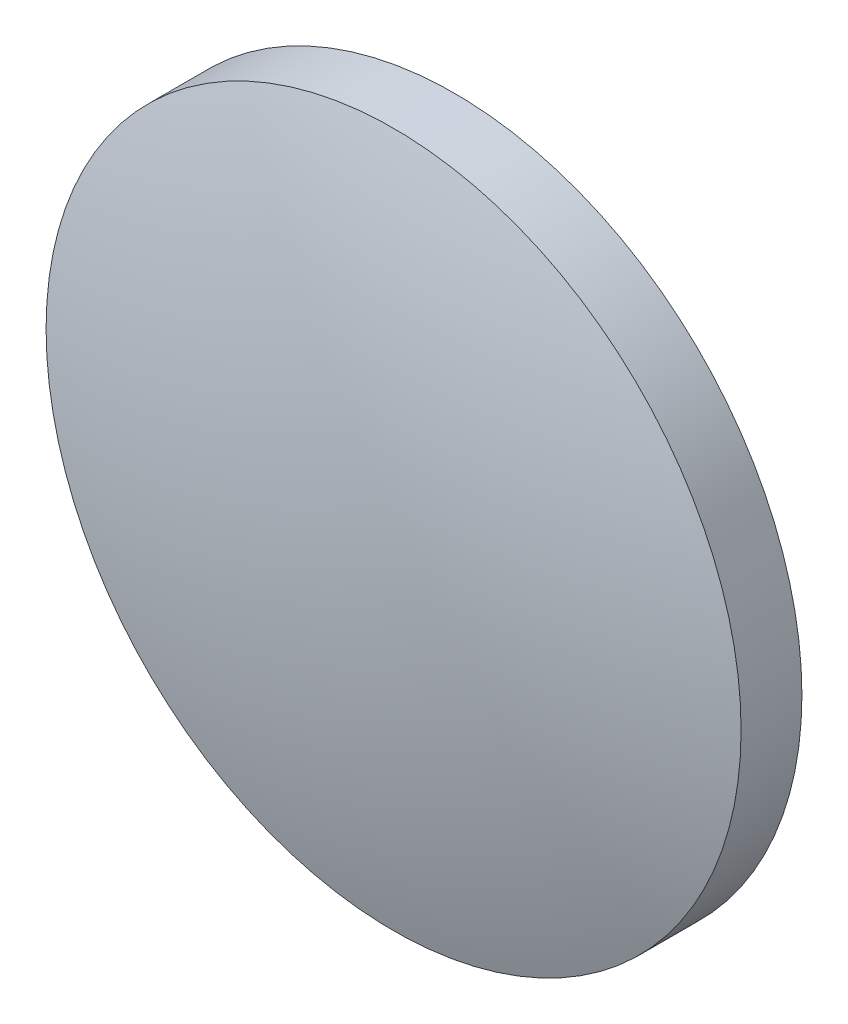
SolidWorks part; units mm, degrees
ref_plane "Front Plane" through (0, 0, 0) normal (0, 0, 1) x (1, 0, 0)
ref_plane "Top Plane" through (0, 0, 0) normal (0, 1, 0) x (1, 0, 0)
ref_plane "Right Plane" through (0, 0, 0) normal (1, 0, 0) x (0, 0, -1)
sketch "Sketch1" plane through (0, 0, 0) normal (0, 0, 1) x (1, 0, 0)
  circle A0 centre (0, 0) radius 20
  dimension "D1" = 40
extrude "Boss-Extrude1" add sketch "Sketch1" along normal blind 2
sketch "Sketch2" plane through (0, 0, 0) normal (1, 0, 0) x (0, 0, -1)
  line L0 (62.9923, 18.1472) -> (62.9923, -18.1472) construction
  line L1 (-2, 20) -> (-2, -20)
  arc A0 (-2, -20) -> (-2, 20) centre (62.9923, 0) cw
  point P3 (-5.0077, 0)
  point P8 (62.9923, 0)
  dimension "D1" = 68
  dimension "D2" = 68
revolve "Revolve1" add sketch "Sketch2" angle 360 about L0
sketch "Sketch3" plane through (0, 0, 0) normal (0, 1, 0) x (1, 0, 0)
  line L1 (76.406, 19.3589) -> (-76.406, 19.3589)
  line L2 (76.406, 19.3589) -> (76.406, 108.8795)
  line L4 (-76.406, 19.3589) -> (-76.406, 108.8795)
  line L5 (76.406, 19.3589) -> (-76.406, 108.8795) construction
  line L6 (76.406, 108.8795) -> (-76.406, 19.3589) construction
  line L7 (76.406, 108.8795) -> (96.4849, 108.8795)
  line L8 (-76.406, 108.8795) -> (-76.406, 197.6245)
  line L9 (-76.406, 197.6245) -> (96.4849, 197.6245)
  line L10 (96.4849, 108.8795) -> (96.4849, 197.6245)
  line L11 (10.0394, 197.6245) -> (10.0394, 153.252) construction
  line L12 (-76.406, 153.252) -> (96.4849, 153.252) construction
  point P0 (0, 64.1192)
  point P112 (10.0394, 153.252)
extrude "Cut-Extrude1" cut sketch "Sketch3" against normal through all both and the other way through all
sketch "Sketch4" plane through (0, 0, 0) normal (0, 0, -1) x (-1, 0, 0)
  circle A0 centre (0, 0) radius 20
  dimension "D1" = 40
extrude "Boss-Extrude2" add sketch "Sketch4" against normal blind 2
sketch "Sketch5" plane through (0, 0, 0) normal (0, 0, -1) x (-1, 0, 0)
  line L0 (70.9455, 20) -> (-70.9455, 20)
  line L1 (70.9455, -20) -> (-70.9455, -20)
  line L2 (-70.9455, 20) -> (-70.9455, -20)
  line L3 (70.9455, -20) -> (70.9455, 20)
  circle A0 centre (0, 0) radius 20
  point P6 (0, 20)
  point P11 (0, -20)
  arc M1 (15.999, 12.0013) -> (-15.999, 12.0013) centre (0, 0) ccw
  arc M3 (-15.999, -12.0013) -> (15.999, -12.0013) centre (0, 0) ccw
  dimension "D1" = 40
extrude "Cut-Extrude2" cut sketch "Sketch5" against normal through all both and the other way through all contours A0 L0 L2 L1 M1 M3 | A0 L1 L3 L0 M3 M1
sketch "Sketch6" plane through (0, 0, 0) normal (0, 0, -1) x (-1, 0, 0)
  circle A0 centre (0, 0) radius 20
extrude "Boss-Extrude3" add sketch "Sketch6" along normal blind 1.5
